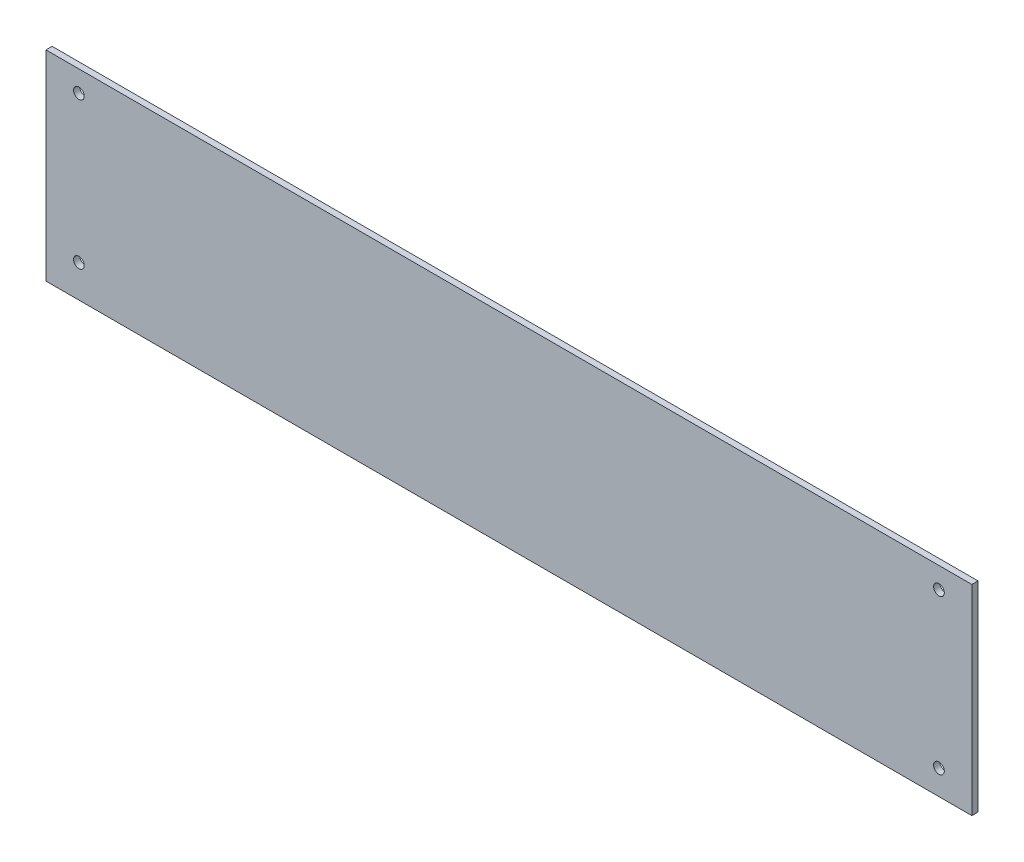
SolidWorks part; units mm, degrees
ref_plane "Plan de face" through (0, 0, 0) normal (0, 0, 1) x (1, 0, 0)
ref_plane "Plan de dessus" through (0, 0, 0) normal (0, 1, 0) x (1, 0, 0)
ref_plane "Plan de droite" through (0, 0, 0) normal (1, 0, 0) x (0, 0, -1)
sketch "Esquisse1" plane through (0, 0, 0) normal (0, 0, 1) x (1, 0, 0)
  line L1 (0, 0) -> (-450.3, 0)
  line L2 (0, 0) -> (0, 97.39)
  line L3 (0, 97.39) -> (-450.3, 97.39)
  line L4 (-450.3, 0) -> (-450.3, 97.39)
  dimension "D1" = 97.39
  dimension "D2" = 450.3
extrude "Boss.-Extru.1" add sketch "Esquisse1" along normal blind 3
sketch "Esquisse2" plane through (0, 0, 3) normal (0, 0, 1) x (1, 0, 0)
  circle A0 centre (-16, 12.0247) radius 2.6 construction
  circle A1 centre (-16, 87.1532) radius 2.6 construction
  circle A2 centre (-434.3, 87.1532) radius 2.6 construction
  circle A3 centre (-434.3, 15.8505) radius 2.6 construction
  circle A4 centre (-16, 12.0247) radius 2.6
  circle A5 centre (-16, 87.1532) radius 2.6
  circle A6 centre (-434.3, 87.1532) radius 2.6
  circle A7 centre (-434.3, 15.8505) radius 2.6
extrude "Enlèv. mat.-Extru.1" cut sketch "Esquisse2" against normal blind 20
